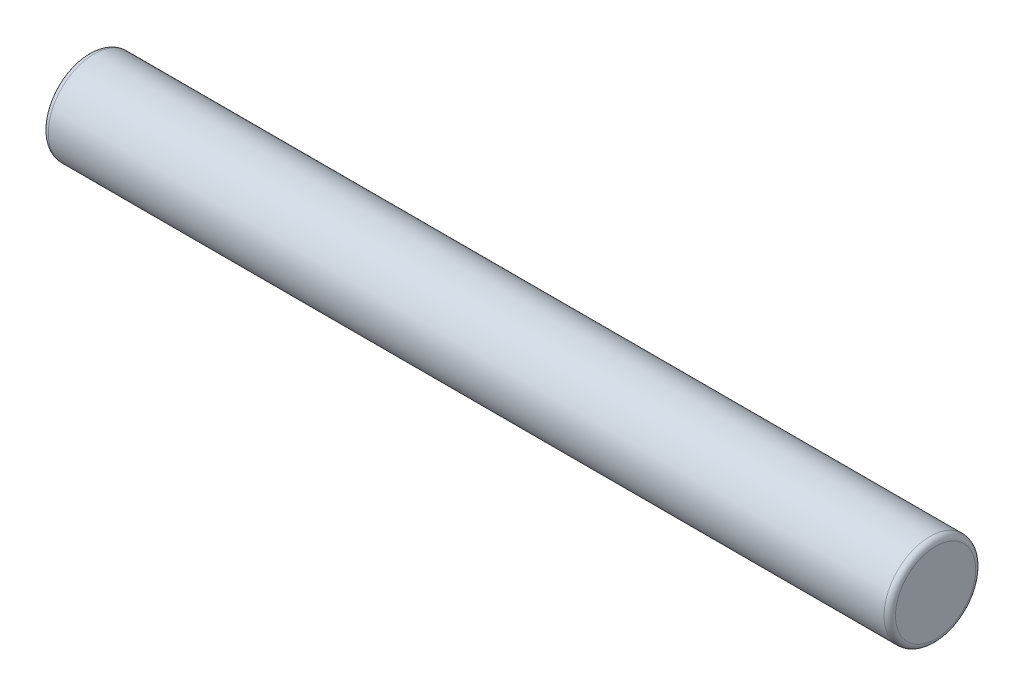
SolidWorks part; units mm, degrees
ref_plane "Front Plane" through (0, 0, 0) normal (0, 0, 1) x (1, 0, 0)
ref_plane "Top Plane" through (0, 0, 0) normal (0, 1, 0) x (1, 0, 0)
ref_plane "Right Plane" through (0, 0, 0) normal (1, 0, 0) x (0, 0, -1)
sketch "Sketch1" plane through (0, 0, 0) normal (1, 0, 0) x (0, 0, -1)
  circle A0 centre (0, 0) radius 1.016
  dimension "D1" = 2.032
extrude "Boss-Extrude1" add sketch "Sketch1" along normal blind 18.796
fillet "Fillet1" radius 0.127 2 edges at (0, 0, -1.016) (18.796, 0, -1.016)
